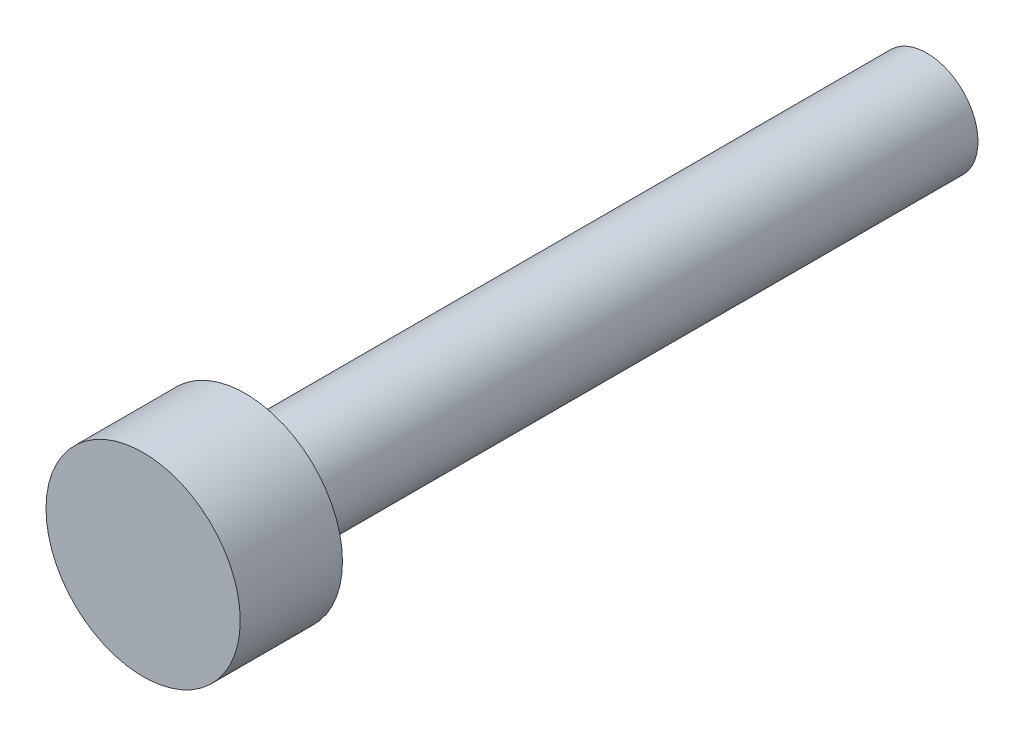
SolidWorks part; units mm, degrees
ref_plane "Front Plane" through (0, 0, 0) normal (0, 0, 1) x (1, 0, 0)
ref_plane "Top Plane" through (0, 0, 0) normal (0, 1, 0) x (1, 0, 0)
ref_plane "Right Plane" through (0, 0, 0) normal (1, 0, 0) x (0, 0, -1)
sketch "Sketch1" plane through (0, 0, 0) normal (0, 0, 1) x (1, 0, 0)
  circle A0 centre (0, 0) radius 1.5
  dimension "D1" = 3
extrude "Boss-Extrude1" add sketch "Sketch1" along normal blind 20
sketch "Sketch2" plane through (0, 0, 20) normal (0, 0, 1) x (1, 0, 0)
  circle A0 centre (0, 0) radius 2.85
  dimension "D1" = 5.7
extrude "Boss-Extrude2" add sketch "Sketch2" along normal blind 3
